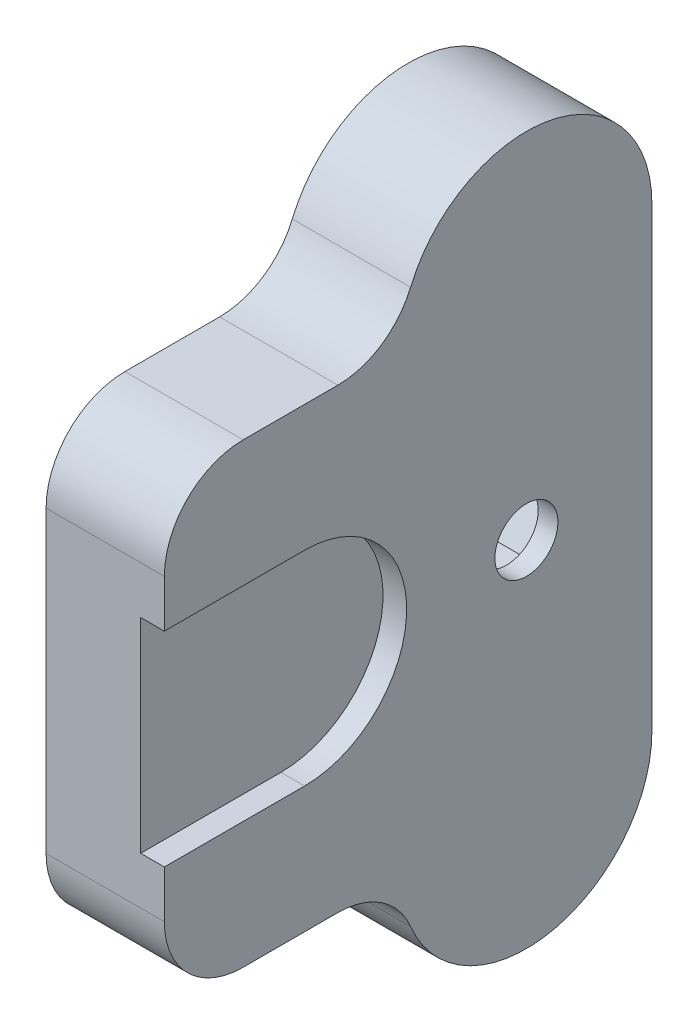
SolidWorks part; units mm, degrees
material "ABS PC"
ref_plane "Front Plane" through (0, 0, 0) normal (1, 0, 0) x (0, 1, 0)
ref_plane "Top Plane" through (0, 0, 0) normal (0, 0, 1) x (0, 1, 0)
ref_plane "Right Plane" through (0, 0, 0) normal (0, 1, 0) x (-1, 0, 0)
sketch "Sketch1" plane through (0, 0, 0) normal (1, 0, 0) x (0, 1, 0)
  line L0 (-28.9545, 0) -> (33.8464, 0) construction
  line L3 (-28.9686, 19.054) -> (-28.9686, -12.7893) construction
  line L4 (0, 49.054) -> (0, -56.7378) construction
  line L6 (-28.9686, -12.7893) -> (28.9686, -12.7893)
  line L7 (44.5791, 0) -> (-44.5791, 0) construction
  line L9 (18.9686, 49.054) -> (-18.9686, 49.054)
  line L12 (-28.9686, 39.054) -> (-28.9686, 27.0474)
  line L13 (28.9686, 19.054) -> (28.9686, -12.7893) construction
  line L14 (28.9686, 39.054) -> (28.9686, 27.0474)
  line L15 (-28.9686, 19.054) -> (28.9686, 19.054) construction
  line L16 (-28.9686, 19.054) -> (28.9686, 19.054) construction
  arc A3 (-35.1108, 17.8215) -> (-28.9686, -12.7893) centre (-28.9686, 3.1323) ccw
  arc A4 (-18.9686, 49.054) -> (-28.9686, 39.054) centre (-18.9686, 39.054) ccw
  arc A5 (-35.1108, 17.8215) -> (-28.9686, 27.0474) centre (-38.9686, 27.0474) ccw
  arc A6 (35.1108, 17.8215) -> (28.9686, 27.0474) centre (38.9686, 27.0474) cw
  arc A7 (18.9686, 49.054) -> (28.9686, 39.054) centre (18.9686, 39.054) cw
  arc A8 (35.1108, 17.8215) -> (28.9686, -12.7893) centre (28.9686, 3.1323) cw
  point P20 (0, 0)
  dimension "D1" = 10
  dimension "D2" = 10
extrude "Boss-Extrude3" add sketch "Sketch1" along normal blind 15
sketch "Sketch3" plane through (15, 0, 0) normal (1, 0, 0) x (0, 1, 0)
  line L0 (-44.8903, 3.1323) -> (44.8903, 3.1323) construction
  line L2 (-28.9686, -12.7893) -> (28.9686, -12.7893) construction
  line L3 (0, -12.7893) -> (0, 49.054) construction
  line L4 (18.9686, 49.054) -> (-18.9686, 49.054) construction
  arc A3 (-35.1108, 17.8215) -> (-28.9686, -12.7893) centre (-28.9686, 3.1323) ccw construction
  arc A4 (28.9686, -12.7893) -> (35.1108, 17.8215) centre (28.9686, 3.1323) ccw construction
  circle A5 centre (0, 3.1323) radius 4
extrude "Cut-Extrude3" cut sketch "Sketch3" against normal blind 14.0462
sketch "Sketch4" plane through (15, 0, 0) normal (1, 0, 0) x (0, 1, 0)
  line L0 (-12.95, 49.054) -> (-12.95, 31.2677)
  line L4 (18.9686, 49.054) -> (-18.9686, 49.054) construction
  line L6 (0, 7.1323) -> (0, 31.2677) construction
  line L7 (12.95, 31.2677) -> (12.95, 49.054)
  line L8 (-12.95, 49.054) -> (12.95, 49.054)
  circle A1 centre (0, 3.1323) radius 4 construction
  circle A2 centre (0, 31.2677) radius 12.95 construction
  arc A3 (-12.95, 31.2677) -> (12.95, 31.2677) centre (0, 31.2677) ccw
extrude "Cut-Extrude4" cut sketch "Sketch4" against normal blind 3
sketch "Sketch5" plane through (15, 0, 0) normal (1, 0, 0) x (0, 1, 0)
  line L0 (-2.9918, 7.8662) -> (2.9918, -1.6015) construction
  line L1 (5.4662, 6.587) -> (-0.2587, 9.5935)
  line L2 (-0.2587, 9.5935) -> (-5.7249, 6.1388)
  line L3 (-5.7249, 6.1388) -> (-5.4662, -0.3223)
  line L4 (-5.4662, -0.3223) -> (0.2587, -3.3288)
  line L5 (0.2587, -3.3288) -> (5.7249, 0.1258)
  line L6 (5.7249, 0.1258) -> (5.4662, 6.587)
  circle A0 centre (0, 3.1323) radius 5.6 construction
  dimension "D1" = 11.2
extrude "Cut-Extrude5" cut sketch "Sketch5" along direction (1, 0, 0) on the side against the normal mid plane 25 from surface at -15 starting at face at (0, 0, 23.7628)
